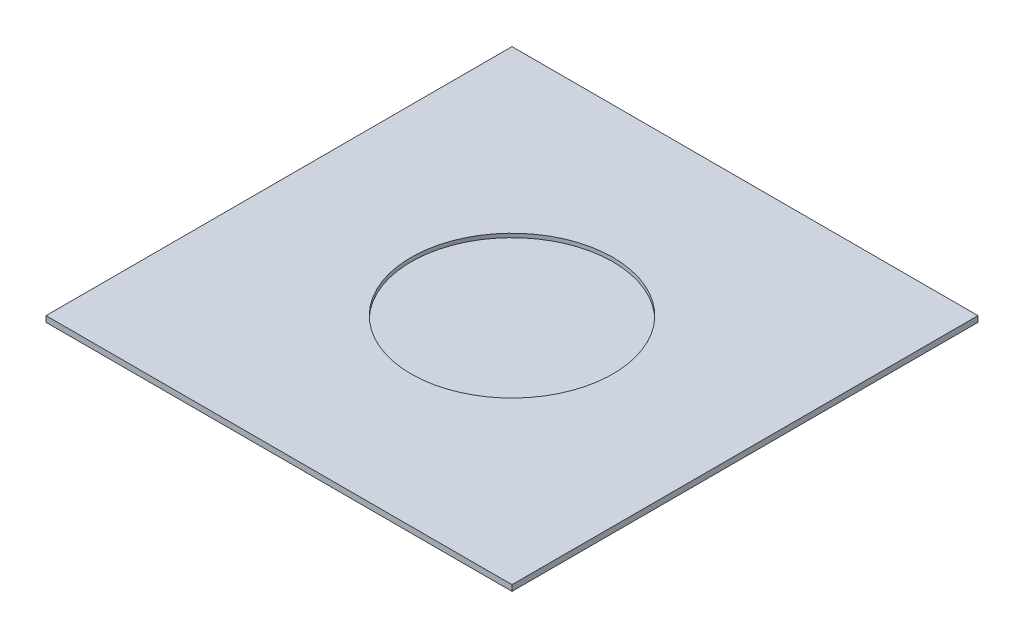
SolidWorks part; units mm, degrees
ref_plane "정면" through (0, 0, 0) normal (0, 0, 1) x (1, 0, 0)
ref_plane "윗면" through (0, 0, 0) normal (0, 1, 0) x (1, 0, 0)
ref_plane "우측면" through (0, 0, 0) normal (1, 0, 0) x (0, 0, -1)
sketch "스케치1" plane through (0, 0, 0) normal (0, 1, 0) x (1, 0, 0)
  line L1 (-600, 600) -> (600, 600)
  line L2 (-600, 600) -> (-600, -600)
  line L3 (-600, -600) -> (600, -600)
  line L4 (600, 600) -> (600, -600)
  line L5 (-600, 600) -> (600, -600) construction
  line L6 (-600, -600) -> (600, 600) construction
  point P0 (0, 0)
extrude "보스-돌출1" add sketch "스케치1" along normal blind 15
sketch "스케치2" plane through (0, 15, 0) normal (0, 1, 0) x (1, 0, 0)
  circle A0 centre (0, 0) radius 260
extrude "컷-돌출1" cut sketch "스케치2" against normal blind 10 contours A0
